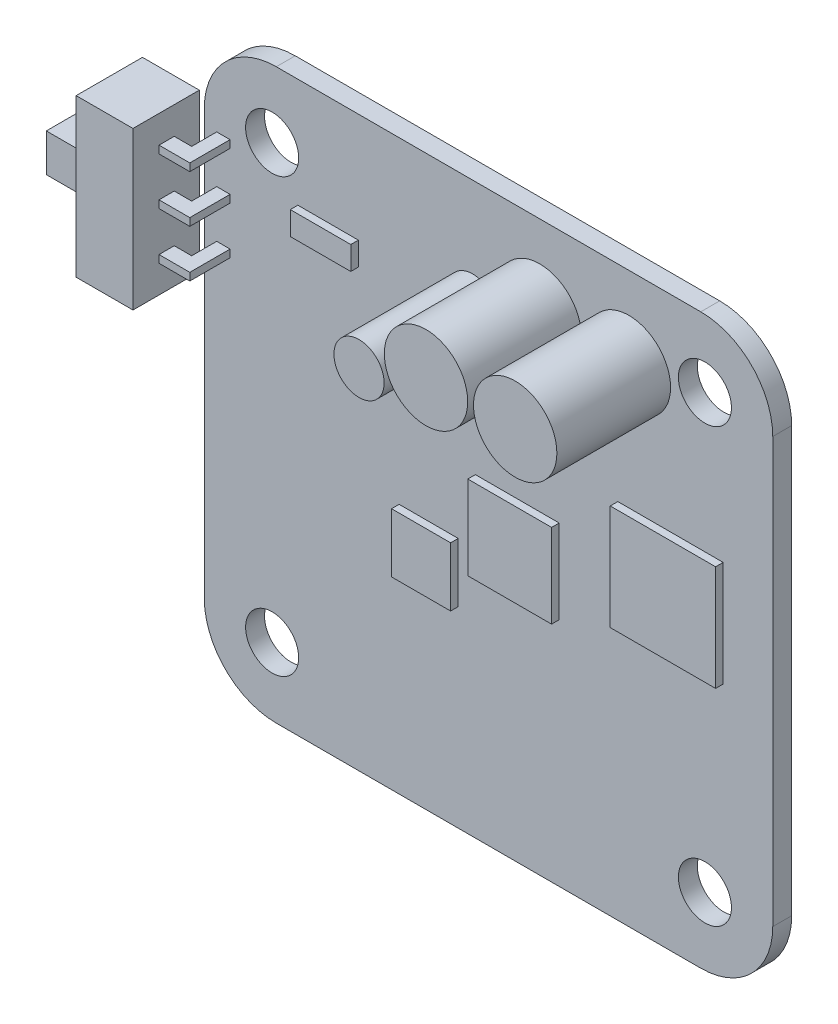
SolidWorks part; units mm, degrees
material "Espuma rígida de poliuretano"
ref_plane "Plano frontal" through (0, 0, 0) normal (0, 0, 1) x (1, 0, 0)
ref_plane "Plano superior" through (0, 0, 0) normal (0, 1, 0) x (1, 0, 0)
ref_plane "Plano direito" through (0, 0, 0) normal (1, 0, 0) x (0, 0, -1)
sketch "Esboço1" plane through (0, 0, 0) normal (0, 0, 1) x (1, 0, 0)
  line L0 (-11.42, 11.42) -> (-11.42, 15) construction
  line L1 (-15, 15) -> (15, 15)
  line L2 (-15, 15) -> (-15, -15)
  line L3 (-15, -15) -> (15, -15)
  line L4 (15, 15) -> (15, -15)
  line L5 (-15, 15) -> (15, -15) construction
  line L6 (-15, -15) -> (15, 15) construction
  line L7 (-11.42, 11.42) -> (-15, 11.42) construction
  line L8 (0, 15) -> (0, -15) construction
  line L10 (-15, 0) -> (15, 0) construction
  circle A0 centre (-11.42, 11.42) radius 1.4
  circle A1 centre (11.42, 11.42) radius 1.4
  circle A2 centre (11.42, -11.42) radius 1.4
  circle A3 centre (-11.42, -11.42) radius 1.4
  point P0 (0, 0)
  dimension "D2" = 2.8
  dimension "D1" = 30
  dimension "D3" = 3.58
extrude "Ressalto-extrusão1" add sketch "Esboço1" along normal blind 1
fillet "Filete1" radius 3.8 4 edges at (15, -15, 0.5) (-15, -15, 0.5) (15, 15, 0.5) (-15, 15, 0.5)
sketch "Esboço2" plane through (0, 0, 1) normal (0, 0, 1) x (1, 0, 0)
  line L1 (-0.695, 1.6111) -> (3.7277, 1.6111)
  line L2 (-0.695, 1.6111) -> (-0.695, -2.8116)
  line L3 (-0.695, -2.8116) -> (3.7277, -2.8116)
  line L4 (3.7277, 1.6111) -> (3.7277, -2.8116)
  line L5 (-0.695, 1.6111) -> (3.7277, -2.8116) construction
  line L6 (-0.695, -2.8116) -> (3.7277, 1.6111) construction
  line L7 (-4.7181, -1.758) -> (-1.6001, -1.758)
  line L8 (-4.7181, -1.758) -> (-4.7181, -4.876)
  line L9 (-4.7181, -4.876) -> (-1.6001, -4.876)
  line L10 (-1.6001, -1.758) -> (-1.6001, -4.876)
  line L11 (-4.7181, -1.758) -> (-1.6001, -4.876) construction
  line L12 (-4.7181, -4.876) -> (-1.6001, -1.758) construction
  line L13 (6.8236, 4.1384) -> (12.3836, 4.1384)
  line L14 (6.8236, 4.1384) -> (6.8236, -1.4216)
  line L15 (6.8236, -1.4216) -> (12.3836, -1.4216)
  line L16 (12.3836, 4.1384) -> (12.3836, -1.4216)
  line L17 (6.8236, 4.1384) -> (12.3836, -1.4216) construction
  line L18 (6.8236, -1.4216) -> (12.3836, 4.1384) construction
  line L19 (-10.0629, 9.2408) -> (-6.8698, 9.2408)
  line L20 (-10.0629, 9.2408) -> (-10.0629, 8.0078)
  line L21 (-10.0629, 8.0078) -> (-6.8698, 8.0078)
  line L22 (-6.8698, 9.2408) -> (-6.8698, 8.0078)
  line L23 (-10.0629, 9.2408) -> (-6.8698, 8.0078) construction
  line L24 (-10.0629, 8.0078) -> (-6.8698, 9.2408) construction
  point P0 (1.5164, -0.6002)
  point P5 (-3.1591, -3.317)
  point P10 (9.6036, 1.3584)
  point P15 (-8.4663, 8.6243)
extrude "Ressalto-extrusão2" add sketch "Esboço2" along normal blind 0.4
sketch "Esboço3" plane through (0, 0, 1) normal (0, 0, 1) x (1, 0, 0)
  line L0 (-15.2626, 10.2487) -> (-13.6386, 10.2487) construction
  line L1 (-18.2626, 11.8987) -> (-15.2626, 11.8987)
  line L2 (-18.2626, 11.8987) -> (-18.2626, 8.7487)
  line L3 (-18.2626, 3.5987) -> (-15.2626, 3.5987)
  line L4 (-15.2626, 11.8987) -> (-15.2626, 10.4487)
  line L5 (-15.2626, 10.0487) -> (-13.6386, 10.0487)
  line L6 (-13.6386, 7.7487) -> (-15.2626, 7.7487) construction
  line L7 (-15.2626, 7.5487) -> (-15.2626, 5.4487) construction
  line L8 (-15.2626, 5.2487) -> (-13.6386, 5.2487) construction
  line L9 (-13.6386, 7.9487) -> (-15.2626, 7.9487)
  line L10 (-15.2626, 5.0487) -> (-13.6386, 5.0487)
  line L11 (-15.2626, 10.4487) -> (-13.6386, 10.4487)
  line L12 (-13.6386, 7.5487) -> (-15.2626, 7.5487)
  line L13 (-15.2626, 5.4487) -> (-13.6386, 5.4487)
  line L14 (-18.2626, 7.7487) -> (-20.5878, 7.7487) construction
  line L15 (-13.6386, 10.0487) -> (-13.6386, 10.4487)
  line L16 (-13.6386, 7.9487) -> (-13.6386, 7.5487)
  line L17 (-18.2626, 8.7487) -> (-20.5878, 8.7487)
  line L19 (-13.6386, 5.0487) -> (-13.6386, 5.4487)
  line L20 (-15.2626, 10.0487) -> (-15.2626, 7.9487)
  line L21 (-15.2626, 7.5487) -> (-15.2626, 5.4487)
  line L22 (-15.2626, 5.0487) -> (-15.2626, 3.5987)
  line L24 (-18.2626, 6.7487) -> (-20.5878, 6.7487)
  line L26 (-20.5878, 8.7487) -> (-20.5878, 6.7487)
  line L27 (-18.2626, 6.7487) -> (-18.2626, 3.5987)
  dimension "D1" = 3
  dimension "D2" = 8.3
  dimension "D3" = 2.5
  dimension "D4" = 2.5
  dimension "D5" = 0.2
  dimension "D6" = 0.2
  dimension "D7" = 1
  dimension "D8" = 1
extrude "Ressalto-extrusão3" add sketch "Esboço3" along normal blind 3.5 separate body
sketch "Esboço4" plane through (0, 0, 1) normal (0, 0, 1) x (1, 0, 0)
  circle A0 centre (7.4069, 10.7421) radius 2.2
  circle A1 centre (2.7012, 10.7421) radius 2.2
  circle A2 centre (-0.8338, 9.3896) radius 1.3244
extrude "Ressalto-extrusão4" add sketch "Esboço4" along normal blind 6
sketch "Esboço6" plane through (0, 3.5987, 0) normal (0, -1, 0) x (1, 0, 0)
  line L0 (-18.2626, 4.5) -> (-18.2626, 1) construction
  line L1 (-15.2626, 4.5) -> (-13.4245, 4.5)
  line L2 (-15.2626, 4.5) -> (-15.2626, 3.1261)
  line L3 (-15.2626, 3.1261) -> (-13.4245, 3.1261)
  line L4 (-13.4245, 4.5) -> (-13.4245, 3.1261)
  line L5 (-15.2626, 1) -> (-14.3435, 1)
  line L6 (-15.2626, 1) -> (-15.2626, 2.323)
  line L7 (-15.2626, 2.323) -> (-14.3435, 2.323)
  line L8 (-14.3435, 1) -> (-14.3435, 2.323)
  line L9 (-20.5878, 3.75) -> (-18.2626, 3.75)
  line L10 (-18.2626, 1.75) -> (-18.2626, 1)
  line L11 (-20.5878, 1.75) -> (-18.2626, 1.75)
  line L13 (-20.5878, 3.75) -> (-18.2626, 1.75) construction
  line L14 (-20.5878, 1.75) -> (-18.2626, 3.75) construction
  line L21 (-20.5878, 1.75) -> (-20.5878, 1)
  line L22 (-20.5878, 4.5) -> (-18.2626, 4.5)
  line L23 (-20.5878, 4.5) -> (-20.5878, 3.75)
  line L24 (-20.5878, 1) -> (-18.2626, 1)
  line L25 (-18.2626, 4.5) -> (-18.2626, 3.75)
  point P10 (-19.4252, 2.75)
  dimension "D1" = 2
extrude "Corte-extrusão1" cut sketch "Esboço6" against normal blind 10
